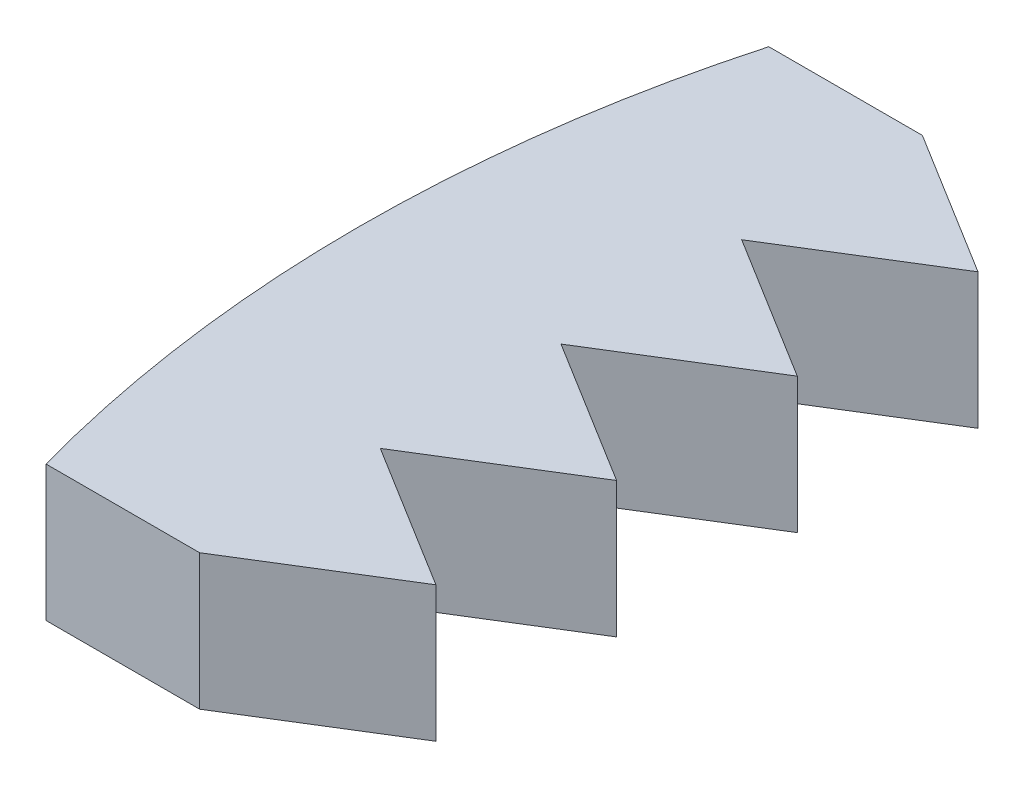
SolidWorks part; units mm, degrees
ref_plane "Front Plane" through (0, 0, 0) normal (0, 0, 1) x (1, 0, 0)
ref_plane "Top Plane" through (0, 0, 0) normal (0, 1, 0) x (1, 0, 0)
ref_plane "Right Plane" through (0, 0, 0) normal (1, 0, 0) x (0, 0, -1)
sketch "Sketch1" plane through (0, 0, 0) normal (0, 1, 0) x (1, 0, 0)
  line L0 (-30.7937, 27.5602) -> (-26.6902, 25.0202)
  line L1 (-26.6902, 25.0202) -> (-30.7937, 22.4802)
  line L2 (-30.7937, 22.4802) -> (-26.6902, 19.9402)
  line L3 (-26.6902, 19.9402) -> (-30.7937, 17.4002)
  line L4 (-30.7937, 17.4002) -> (-26.6902, 14.8602)
  line L5 (-26.6902, 14.8602) -> (-30.7937, 12.3202)
  line L6 (-30.7937, 12.3202) -> (-26.6902, 9.7802)
  line L7 (-26.6902, 9.7802) -> (-30.7937, 7.2402)
  line L8 (-30.7937, 7.2402) -> (-35.1117, 7.2402)
  line L10 (-35.1117, 27.5602) -> (-30.7937, 27.5602)
  line L11 (-30.7937, 17.4002) -> (-34.8407, 17.4002) construction
  arc A1 (-35.1117, 27.5602) -> (-35.1117, 7.2402) centre (1.6086, 17.4002) ccw
  dimension "D4" = 76.2
  dimension "D3" = 4.318
  dimension "D1" = 4.826
  dimension "D2" = 5.08
extrude "Boss-Extrude1" add sketch "Sketch1" along normal blind 3.81
